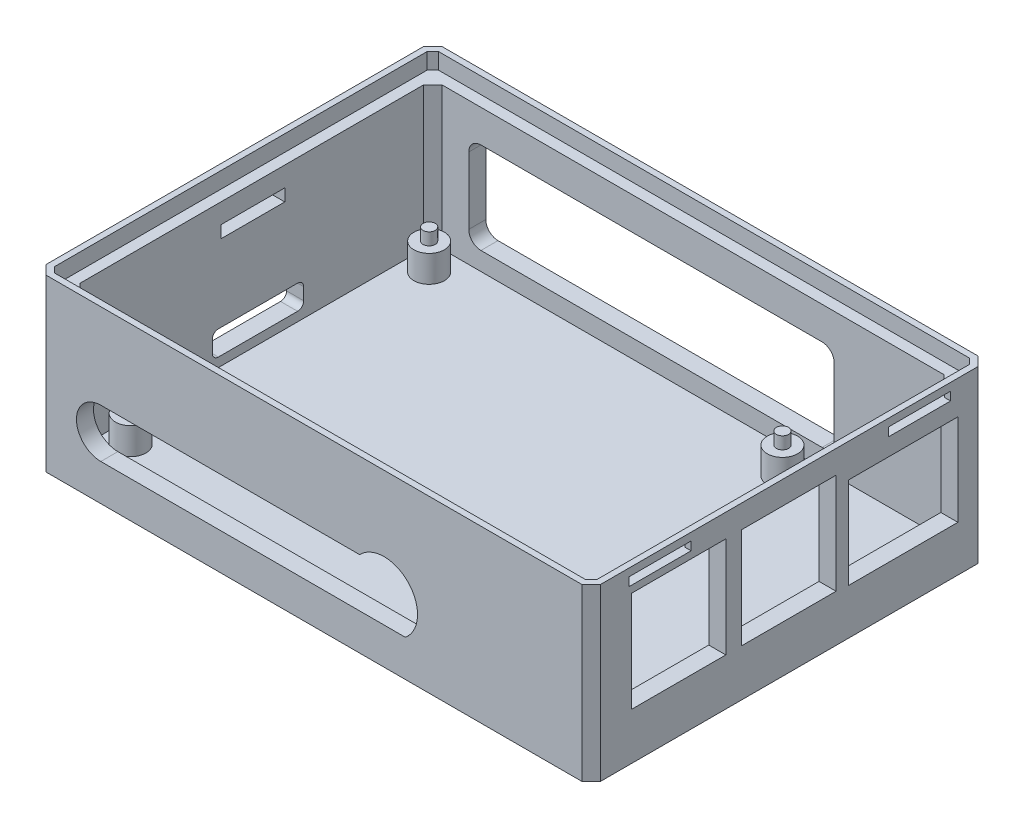
SolidWorks part; units mm, degrees
ref_plane "Front Plane" through (0, 0, 0) normal (0, 0, 1) x (1, 0, 0)
ref_plane "Top Plane" through (0, 0, 0) normal (0, 1, 0) x (1, 0, 0)
ref_plane "Right Plane" through (0, 0, 0) normal (1, 0, 0) x (0, 0, -1)
sketch "Sketch1" plane through (0, 0, 0) normal (0, 1, 0) x (1, 0, 0)
  line L1 (-45.5, -32.5) -> (45.5, -32.5)
  line L2 (-45.5, -32.5) -> (-45.5, 32.5)
  line L3 (-45.5, 32.5) -> (45.5, 32.5)
  line L4 (45.5, -32.5) -> (45.5, 32.5)
  line L5 (-45.5, -32.5) -> (45.5, 32.5) construction
  line L6 (-45.5, 32.5) -> (45.5, -32.5) construction
  point P0 (0, 0)
  dimension "D1" = 65
  dimension "D2" = 91
extrude "Boss-Extrude1" add sketch "Sketch1" along normal blind 2
sketch "Sketch2" plane through (0, 2, 0) normal (0, 1, 0) x (1, 0, 0)
  circle A0 centre (-39, -23.6) radius 2.5
  circle A1 centre (-39, 25.4) radius 2.5
  circle A2 centre (19, 25.4) radius 2.5
  circle A3 centre (19, -23.6) radius 2.5
  dimension "D1" = 5
extrude "Boss-Extrude2" add sketch "Sketch2" along normal blind 4.4
sketch "Sketch3" plane through (0, 6.4, 0) normal (0, 1, 0) x (1, 0, 0)
  circle A0 centre (-39, -23.6) radius 1
  circle A1 centre (-39, 25.4) radius 1
  circle A2 centre (19, 25.4) radius 1
  circle A3 centre (19, -23.6) radius 1
  dimension "D1" = 2
extrude "Boss-Extrude3" add sketch "Sketch3" along normal blind 2
sketch "Sketch4" plane through (0, 0, 32.5) normal (0, 0, 1) x (1, 0, 0)
  line L0 (45.5, 2) -> (45.5, 0) construction
  line L1 (-45.5, 0) -> (45.5, 0)
  line L2 (-45.5, 0) -> (-45.5, 28)
  line L3 (-45.5, 28) -> (45.5, 28)
  line L4 (45.5, 0) -> (45.5, 28)
  line L5 (-45.5, 0) -> (45.5, 28) construction
  line L6 (-45.5, 28) -> (45.5, 0) construction
  line L7 (-35, 10) -> (15, 10) construction
  line L8 (-35, 14) -> (7.5, 14)
  line L9 (-35, 6) -> (15, 6)
  line L11 (7.5, 14) -> (15, 14) construction
  arc A0 (-35, 14) -> (-35, 6) centre (-35, 10) ccw
  arc A1 (15, 6) -> (15.5258, 13.9653) centre (15, 10) ccw construction
  arc A2 (15.5258, 13.9653) -> (7.5, 14) centre (11.5, 11) ccw construction
  arc A3 (7.5, 14) -> (6.5951, 11.9707) centre (11.5, 11) ccw construction
  arc A4 (6.5951, 11.9707) -> (6.601, 10) centre (11.5, 11) ccw construction
  arc A5 (6.601, 10) -> (11.5, 6) centre (11.5, 11) ccw construction
  arc A6 (11.5, 6) -> (16.1022, 9.0455) centre (11.5, 11) ccw construction
  arc A7 (16.1022, 9.0455) -> (15.5258, 13.9653) centre (11.5, 11) ccw construction
  arc A8 (15.5258, 13.9653) -> (15, 14) centre (15, 10) ccw construction
  arc A9 (15, 6) -> (7.5, 14) centre (11.5, 10.2344) ccw
  arc A10 (8, 6) -> (15, 6) centre (11.5, 10.2344) ccw construction
  arc A11 (6.0114, 10) -> (8, 6) centre (11.5, 10.2344) ccw construction
  arc A12 (6.3173, 12.0562) -> (6.0114, 10) centre (11.5, 10.2344) ccw construction
  arc A13 (7.5, 14) -> (6.3173, 12.0562) centre (11.5, 10.2344) ccw construction
  point P4 (0, 14)
  point P10 (-10, 10)
  dimension "D2" = 4
  dimension "D6" = 4
  dimension "D7" = 5
  dimension "D8" = 29.9742
  dimension "D9" = 30.5
  dimension "D10" = 30.5
  dimension "D11" = 38
  dimension "D12" = 34
  dimension "D1" = 28
  dimension "D3" = 50
  dimension "D4" = 10
  dimension "D5" = 10
extrude "Boss-Extrude4" add sketch "Sketch4" against normal blind 2.8
sketch "Sketch5" plane through (45.5, 0, 0) normal (1, 0, 0) x (0, 0, -1)
  line L1 (-32.5, 28) -> (32.5, 28)
  line L2 (-32.5, 28) -> (-32.5, 0)
  line L3 (-32.5, 0) -> (32.5, 0)
  line L4 (32.5, 28) -> (32.5, 0)
  line L5 (-32.5, 28) -> (32.5, 0) construction
  line L6 (-32.5, 0) -> (32.5, 28) construction
  line L7 (-25.9, 24.2) -> (-10.4, 24.2)
  line L8 (-25.9, 24.2) -> (-25.9, 7.7)
  line L9 (-25.9, 7.7) -> (-10.4, 7.7)
  line L10 (-10.4, 24.2) -> (-10.4, 7.7)
  line L11 (-25.9, 24.2) -> (-10.4, 7.7) construction
  line L12 (-25.9, 7.7) -> (-10.4, 24.2) construction
  line L13 (-7.8, 24.2) -> (7.7, 24.2)
  line L14 (-7.8, 24.2) -> (-7.8, 7.7)
  line L15 (-7.8, 7.7) -> (7.7, 7.7)
  line L16 (7.7, 24.2) -> (7.7, 7.7)
  line L17 (-7.8, 24.2) -> (7.7, 7.7) construction
  line L18 (-7.8, 7.7) -> (7.7, 24.2) construction
  line L19 (9.7, 22.5) -> (27.7, 22.5)
  line L20 (9.7, 22.5) -> (9.7, 7.5)
  line L21 (9.7, 7.5) -> (27.7, 7.5)
  line L22 (27.7, 22.5) -> (27.7, 7.5)
  line L23 (9.7, 22.5) -> (27.7, 7.5) construction
  line L24 (9.7, 7.5) -> (27.7, 22.5) construction
  point P4 (0, 14)
  point P11 (-18.15, 15.95)
  point P16 (-0.05, 15.95)
  point P21 (18.7, 15)
  dimension "D1" = 15.5
  dimension "D2" = 15.5
  dimension "D3" = 18
  dimension "D4" = 16.5
  dimension "D5" = 16.5
  dimension "D6" = 15
  dimension "D7" = 3.8
  dimension "D8" = 6.6
  dimension "D9" = 2.6
  dimension "D10" = 2
  dimension "D11" = 5.5
extrude "Boss-Extrude5" add sketch "Sketch5" against normal blind 2.8
sketch "Sketch6" plane through (0, 0, -32.5) normal (0, 0, -1) x (-1, 0, 0)
  line L1 (-45.5, 28) -> (45.5, 28)
  line L2 (-45.5, 28) -> (-45.5, 0)
  line L3 (-45.5, 0) -> (45.5, 0)
  line L4 (45.5, 28) -> (45.5, 0)
  line L5 (-45.5, 28) -> (45.5, 0) construction
  line L6 (-45.5, 0) -> (45.5, 28) construction
  line L7 (-21.2, 20) -> (34.8, 20)
  line L8 (-23.2, 18) -> (-23.2, 7)
  line L9 (-21.2, 5) -> (34.8, 5)
  line L10 (36.8, 18) -> (36.8, 7)
  line L11 (-23.2, 20) -> (36.8, 5) construction
  line L12 (-23.2, 5) -> (36.8, 20) construction
  arc A0 (34.8, 5) -> (36.8, 7) centre (34.8, 7) ccw
  arc A1 (-23.2, 7) -> (-21.2, 5) centre (-21.2, 7) ccw
  arc A2 (34.8, 20) -> (36.8, 18) centre (34.8, 18) cw
  arc A3 (-21.2, 20) -> (-23.2, 18) centre (-21.2, 18) ccw
  point P4 (0, 14)
  point P11 (6.8, 12.5)
  dimension "D5" = 2
  dimension "D1" = 60
  dimension "D2" = 15
  dimension "D3" = 5
  dimension "D4" = 6.8
extrude "Boss-Extrude6" add sketch "Sketch6" against normal blind 2.8
sketch "Sketch7" plane through (-45.5, 0, 0) normal (-1, 0, 0) x (0, 0, 1)
  line L1 (-32.5, 28) -> (32.5, 28)
  line L2 (-32.5, 28) -> (-32.5, 0)
  line L3 (-32.5, 0) -> (32.5, 0)
  line L4 (32.5, 28) -> (32.5, 0)
  line L5 (-32.5, 28) -> (32.5, 0) construction
  line L6 (-32.5, 0) -> (32.5, 28) construction
  line L7 (-7.5, 3.5) -> (5.5, 3.5)
  line L8 (-8.5, 4.5) -> (-8.5, 6.5)
  line L9 (-7.5, 7.5) -> (5.5, 7.5)
  line L10 (6.5, 4.5) -> (6.5, 6.5)
  line L11 (-8.5, 3.5) -> (6.5, 7.5) construction
  line L12 (-8.5, 7.5) -> (6.5, 3.5) construction
  arc A0 (5.5, 7.5) -> (6.5, 6.5) centre (5.5, 6.5) cw
  arc A1 (5.5, 3.5) -> (6.5, 4.5) centre (5.5, 4.5) ccw
  arc A2 (-7.5, 3.5) -> (-8.5, 4.5) centre (-7.5, 4.5) cw
  arc A3 (-8.5, 6.5) -> (-7.5, 7.5) centre (-7.5, 6.5) cw
  point P4 (0, 14)
  point P11 (-1, 5.5)
  dimension "D5" = 1
  dimension "D1" = 15
  dimension "D2" = 4
  dimension "D3" = 1
  dimension "D4" = 5.5
extrude "Boss-Extrude7" add sketch "Sketch7" against normal blind 2.8
chamfer "Chamfer1" distance 1.5 angle 45 8 edges at (45.5, 14, -32.5) (-45.5, 14, -32.5) (-45.5, 14, 32.5) (-42.7, 15, 29.7) (42.7, 15, -29.7) (-42.7, 15, -29.7) (45.5, 14, 32.5) (42.7, 15, 29.7)
sketch "Sketch8" plane through (0, 28, 0) normal (0, 1, 0) x (1, 0, 0)
  line L0 (43.5858, 31.5) -> (-43.5858, 31.5)
  line L1 (-43.5858, 31.5) -> (-44.5, 30.5858)
  line L2 (-44.5, 30.5858) -> (-44.5, -30.5858)
  line L3 (-44.5, -30.5858) -> (-43.5858, -31.5)
  line L4 (-43.5858, -31.5) -> (43.5858, -31.5)
  line L5 (43.5858, -31.5) -> (44.5, -30.5858)
  line L6 (44.5, -30.5858) -> (44.5, 30.5858)
  line L7 (44.5, 30.5858) -> (43.5858, 31.5)
  line L8 (45.5, -31) -> (45.5, 31)
  line L9 (45.5, 31) -> (44, 32.5)
  line L10 (44, 32.5) -> (-44, 32.5)
  line L11 (-44, 32.5) -> (-45.5, 31)
  line L12 (-45.5, 31) -> (-45.5, -31)
  line L13 (-45.5, -31) -> (-44, -32.5)
  line L14 (-44, -32.5) -> (44, -32.5)
  line L15 (44, -32.5) -> (45.5, -31)
  line L16 (45.5, -31) -> (45.5, 31)
  line L17 (45.5, 31) -> (44, 32.5)
  line L18 (44, 32.5) -> (-44, 32.5)
  line L19 (-44, 32.5) -> (-45.5, 31)
  line L20 (-45.5, 31) -> (-45.5, -31)
  line L21 (-45.5, -31) -> (-44, -32.5)
  line L22 (-44, -32.5) -> (44, -32.5)
  line L23 (44, -32.5) -> (45.5, -31)
  dimension "D1" = 0
  dimension "D2" = 1
extrude "Cut-Extrude1" cut sketch "Sketch8" against normal blind 2.65 contours L0 L1 L2 L3 L4 L5 L6 L7
sketch "Sketch11" plane through (-42.7, 0, 0) normal (1, 0, 0) x (0, 0, -1)
  line L1 (-5.1, 22.1) -> (5.4, 22.1)
  line L2 (-5.1, 22.1) -> (-5.1, 20.1)
  line L3 (-5.1, 20.1) -> (5.4, 20.1)
  line L4 (5.4, 22.1) -> (5.4, 20.1)
  line L5 (-5.1, 22.1) -> (5.4, 20.1) construction
  line L6 (-5.1, 20.1) -> (5.4, 22.1) construction
  point P4 (0.15, 21.1)
  dimension "D1" = 10.5
  dimension "D2" = 2
  dimension "D3" = 5.1
  dimension "D4" = 21.1
extrude "Cut-Extrude2" cut sketch "Sketch11" against normal blind 3
sketch "Sketch12" plane through (45.5, 0, 0) normal (1, 0, 0) x (0, 0, -1)
  line L0 (28.2, 25.35) -> (-28.2, 25.35) construction
  line L1 (-16.1, 25.35) -> (-26.3, 25.35)
  line L2 (-16.1, 25.35) -> (-16.1, 26.75)
  line L3 (-16.1, 26.75) -> (-26.3, 26.75)
  line L4 (-26.3, 25.35) -> (-26.3, 26.75)
  line L5 (-16.1, 25.35) -> (-26.3, 26.75) construction
  line L6 (-16.1, 26.75) -> (-26.3, 25.35) construction
  line L7 (-32.5, 0) -> (-32.5, 28) construction
  line L8 (26.5, 25.35) -> (16.3, 25.35)
  line L9 (26.5, 25.35) -> (26.5, 26.75)
  line L10 (26.5, 26.75) -> (16.3, 26.75)
  line L11 (16.3, 25.35) -> (16.3, 26.75)
  line L12 (26.5, 25.35) -> (16.3, 26.75) construction
  line L13 (26.5, 26.75) -> (16.3, 25.35) construction
  line L14 (32.5, 28) -> (32.5, 0) construction
  point P4 (-21.2, 26.05)
  point P11 (21.4, 26.05)
  dimension "D1" = 10.2
  dimension "D2" = 1.4
  dimension "D3" = 1.4
  dimension "D4" = 10.2
  dimension "D5" = 6.2
  dimension "D6" = 6
extrude "Cut-Extrude3" cut sketch "Sketch12" against normal blind 3
